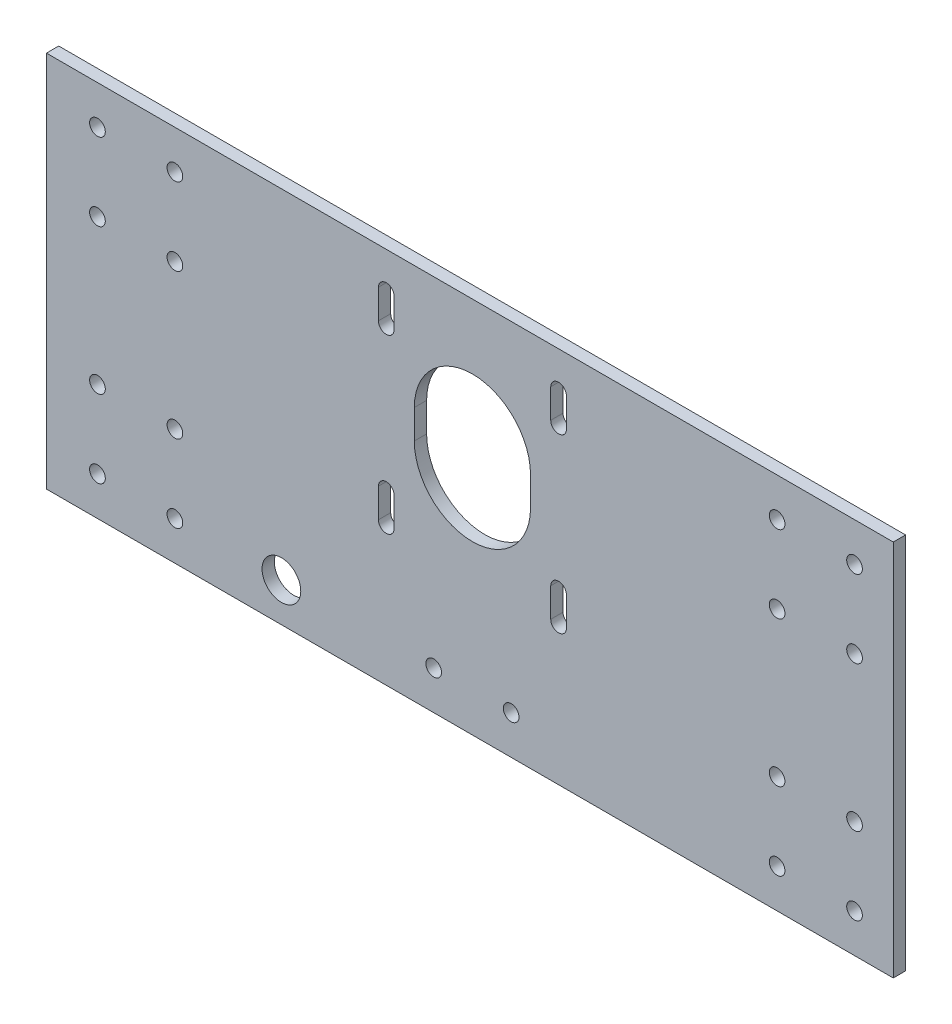
SolidWorks part; units mm, degrees
material "AISI Type A2 Tool Steel"
ref_plane "Front Plane" through (0, 0, 0) normal (0, 0, 1) x (1, 0, 0)
ref_plane "Top Plane" through (0, 0, 0) normal (0, 1, 0) x (1, 0, 0)
ref_plane "Right Plane" through (0, 0, 0) normal (1, 0, 0) x (0, 0, -1)
sketch "Sketch1" plane through (0, 0, 0) normal (0, 0, 1) x (1, 0, 0)
  line L0 (-44.5, -44.5) -> (-44.5, -29.5) construction
  line L1 (-44.5, 44.5) -> (44.5, 44.5) construction
  line L2 (-44.5, 44.5) -> (-44.5, -44.5) construction
  line L3 (-44.5, -44.5) -> (44.5, -44.5) construction
  line L4 (44.5, 44.5) -> (44.5, -44.5) construction
  line L5 (-44.5, 44.5) -> (44.5, -44.5) construction
  line L6 (-44.5, -44.5) -> (44.5, 44.5) construction
  line L7 (-48.55, -44.5) -> (-48.55, -29.5)
  line L8 (-40.45, -44.5) -> (-40.45, -29.5)
  line L9 (-44.5, 44.5) -> (-44.5, 59.5) construction
  line L10 (-48.55, 44.5) -> (-48.55, 59.5)
  line L11 (-40.45, 44.5) -> (-40.45, 59.5)
  line L12 (44.5, 44.5) -> (44.5, 59.5) construction
  line L13 (40.45, 44.5) -> (40.45, 59.5)
  line L14 (48.55, 44.5) -> (48.55, 59.5)
  line L15 (44.5, -44.5) -> (44.5, -29.5) construction
  line L16 (40.45, -44.5) -> (40.45, -29.5)
  line L17 (48.55, -44.5) -> (48.55, -29.5)
  line L18 (0, 0) -> (0, 15) construction
  line L19 (-30, 0) -> (-30, 15)
  line L20 (30, 0) -> (30, 15)
  line L21 (-220, -116.5) -> (217.35, -116.5)
  line L22 (217.35, -116.5) -> (217.35, 78.5)
  line L23 (217.35, 78.5) -> (-220, 78.5)
  line L24 (-220, 78.5) -> (-220, -116.5)
  line L25 (-173.65, 38.5) -> (-173.65, -76.5) construction
  line L26 (-193.65, -56.5) -> (-153.65, -56.5) construction
  line L27 (-193.65, -56.5) -> (-193.65, -96.5) construction
  line L28 (-193.65, -96.5) -> (-153.65, -96.5) construction
  line L29 (-153.65, -56.5) -> (-153.65, -96.5) construction
  line L30 (-193.65, -56.5) -> (-153.65, -96.5) construction
  line L31 (-193.65, -96.5) -> (-153.65, -56.5) construction
  line L32 (-193.65, 18.5) -> (-153.65, 18.5) construction
  line L33 (-193.65, 18.5) -> (-193.65, 58.5) construction
  line L34 (-193.65, 58.5) -> (-153.65, 58.5) construction
  line L35 (-153.65, 18.5) -> (-153.65, 58.5) construction
  line L36 (-193.65, 18.5) -> (-153.65, 58.5) construction
  line L37 (-193.65, 58.5) -> (-153.65, 18.5) construction
  line L38 (197.35, -96.5) -> (157.35, -96.5) construction
  line L39 (197.35, -96.5) -> (197.35, -56.5) construction
  line L40 (197.35, -56.5) -> (157.35, -56.5) construction
  line L41 (157.35, -96.5) -> (157.35, -56.5) construction
  line L42 (197.35, -96.5) -> (157.35, -56.5) construction
  line L43 (197.35, -56.5) -> (157.35, -96.5) construction
  line L44 (197.35, 18.5) -> (157.35, 18.5) construction
  line L45 (197.35, 18.5) -> (197.35, 58.5) construction
  line L46 (197.35, 58.5) -> (157.35, 58.5) construction
  line L47 (157.35, 18.5) -> (157.35, 58.5) construction
  line L48 (197.35, 18.5) -> (157.35, 58.5) construction
  line L49 (197.35, 58.5) -> (157.35, 18.5) construction
  line L50 (-20, -96.5) -> (20, -96.5) construction
  line L51 (177.35, 38.5) -> (177.35, -76.5) construction
  line L52 (-213.65, -42.4115) -> (-133.65, -42.4115) construction
  line L53 (-213.65, -42.4115) -> (-213.65, -110.5885) construction
  line L54 (-213.65, -110.5885) -> (-133.65, -110.5885) construction
  line L55 (-133.65, -42.4115) -> (-133.65, -110.5885) construction
  line L56 (-213.65, -42.4115) -> (-133.65, -110.5885) construction
  line L57 (-213.65, -110.5885) -> (-133.65, -42.4115) construction
  line L58 (0, -96.5) -> (0, -116.5) construction
  arc A0 (-48.55, -44.5) -> (-40.45, -44.5) centre (-44.5, -44.5) ccw
  arc A1 (-40.45, -29.5) -> (-48.55, -29.5) centre (-44.5, -29.5) ccw
  arc A2 (-48.55, 44.5) -> (-40.45, 44.5) centre (-44.5, 44.5) ccw
  arc A3 (-40.45, 59.5) -> (-48.55, 59.5) centre (-44.5, 59.5) ccw
  arc A4 (40.45, 44.5) -> (48.55, 44.5) centre (44.5, 44.5) ccw
  arc A5 (48.55, 59.5) -> (40.45, 59.5) centre (44.5, 59.5) ccw
  arc A6 (40.45, -44.5) -> (48.55, -44.5) centre (44.5, -44.5) ccw
  arc A7 (48.55, -29.5) -> (40.45, -29.5) centre (44.5, -29.5) ccw
  arc A8 (-30, 0) -> (30, 0) centre (0, 0) ccw
  arc A9 (30, 15) -> (-30, 15) centre (0, 15) ccw
  circle A10 centre (-193.65, 58.5) radius 4.05
  circle A11 centre (-153.65, 58.5) radius 4.05
  circle A12 centre (-153.65, 18.5) radius 4.05
  circle A13 centre (-193.65, 18.5) radius 4.05
  circle A14 centre (-193.65, -56.5) radius 4.05
  circle A15 centre (-153.65, -56.5) radius 4.05
  circle A16 centre (-153.65, -96.5) radius 4.05
  circle A17 centre (-193.65, -96.5) radius 4.05
  circle A18 centre (157.35, -56.5) radius 4.05
  circle A19 centre (197.35, -56.5) radius 4.05
  circle A20 centre (197.35, -96.5) radius 4.05
  circle A21 centre (157.35, -96.5) radius 4.05
  circle A22 centre (157.35, 18.5) radius 4.05
  circle A23 centre (197.35, 18.5) radius 4.05
  circle A24 centre (197.35, 58.5) radius 4.05
  circle A25 centre (157.35, 58.5) radius 4.05
  circle A26 centre (-98.65, -96.5) radius 10
  circle A27 centre (-20, -96.5) radius 4.05
  circle A28 centre (20, -96.5) radius 4.05
  point P0 (0, 0)
  point P6 (-44.5, -37)
  point P12 (-44.5, 52)
  point P18 (44.5, 52)
  point P24 (44.5, -37)
  point P30 (0, 7.5)
  point P39 (-173.65, -76.5)
  point P46 (-173.65, 38.5)
  point P51 (177.35, -76.5)
  point P56 (177.35, 38.5)
  point P82 (-173.65, -96.5)
  dimension "D10" = 8.1
  dimension "D20" = 20
  dimension "D24" = 8.1
  dimension "D1" = 89
  dimension "D2" = 8.1
  dimension "D3" = 15
  dimension "D4" = 15
  dimension "D5" = 60
  dimension "D6" = 220
  dimension "D7" = 437.35
  dimension "D8" = 72
  dimension "D9" = 195
  dimension "D11" = 40
  dimension "D12" = 26.35
  dimension "D13" = 20
  dimension "D14" = 20
  dimension "D15" = 20
  dimension "D16" = 20
  dimension "D17" = 20
  dimension "D18" = 80
  dimension "D19" = 35
  dimension "D21" = 20
  dimension "D22" = 20
  dimension "D23" = 40
extrude "Boss-Extrude1" add sketch "Sketch1" along normal blind 6.35
